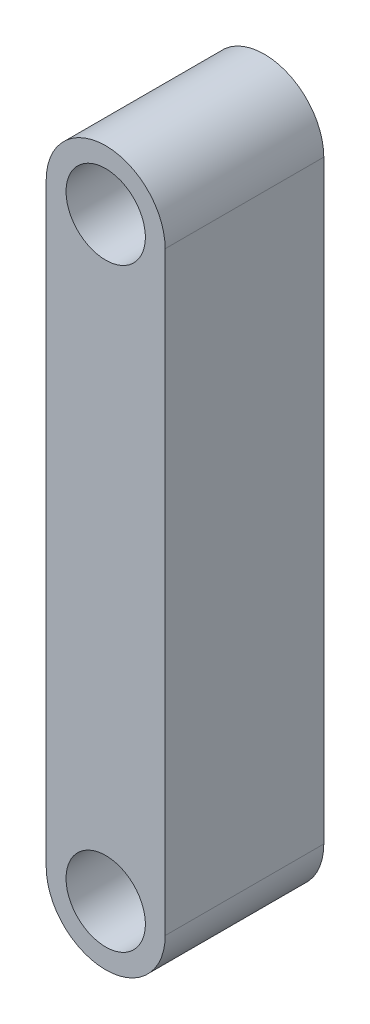
SolidWorks part; units mm, degrees
ref_plane "Front Plane" through (0, 0, 0) normal (0, 0, 1) x (1, 0, 0)
ref_plane "Top Plane" through (0, 0, 0) normal (0, 1, 0) x (1, 0, 0)
ref_plane "Right Plane" through (0, 0, 0) normal (1, 0, 0) x (0, 0, -1)
sketch "Sketch1" plane through (0, 0, 0) normal (0, 0, 1) x (1, 0, 0)
  line L2 (-3, 15) -> (-3, -15)
  line L4 (3, 15) -> (3, -15)
  arc A0 (3, 15) -> (-3, 15) centre (0, 15) ccw
  arc A1 (-3, -15) -> (3, -15) centre (0, -15) ccw
  point P5 (0, 0)
  point P7 (-3, 0)
  point P8 (0, 0)
  point P9 (0, 0)
  point P11 (3, 0)
  point P12 (-3, 15)
  point P13 (0, 0)
  dimension "D2" = 6
  dimension "D1" = 30
extrude "Boss-Extrude1" add sketch "Sketch1" along normal blind 8 contours A0 L2 A1 L4
hole_wizard "Ø4.0 mm Dowel Holes1" positions "Sketch2" profile "Sketch3" hole size "Ø4.0" standard "ISO" end condition through all
sketch "Sketch2" plane through (0, 0, 0) normal (0, 0, -1) x (-1, 0, 0)
  point P0 (0, 15)
sketch "Sketch3" plane through (0, 15, 0) normal (1, 0, 0) x (0, 1, 0)
  line L0 (0, 0) -> (0, 8)
  line L1 (0, 8) -> (2, 8)
  line L2 (2, 8) -> (2, 0)
  line L5 (2, 0) -> (0, 0)
  line L11 (0, -6.35) -> (0, 107.95) construction
  dimension "Thru Hole Dia." = 4
  dimension "Thru Hole Depth" = 8
mirror "Mirror1" about plane through (0, 0, 0) normal (0, 1, 0) of "Ø4.0 mm Dowel Holes1"
